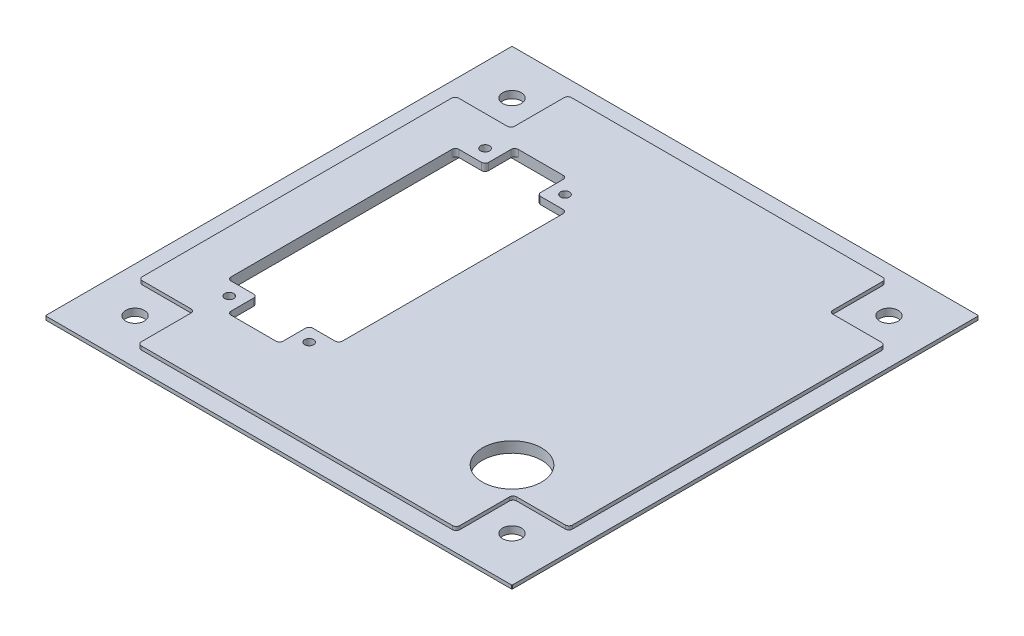
SolidWorks part; units mm, degrees
ref_plane "Front Plane" through (0, 0, 0) normal (0, 0, 1) x (1, 0, 0)
ref_plane "Top Plane" through (0, 0, 0) normal (0, 1, 0) x (1, 0, 0)
ref_plane "Right Plane" through (0, 0, 0) normal (1, 0, 0) x (0, 0, -1)
other "Configuration Table"
sketch "草图1" plane through (0, 0, 0) normal (0, 1, 0) x (1, 0, 0)
  line L1 (-65, 65) -> (65, 65)
  line L2 (-65, 65) -> (-65, -65)
  line L3 (-65, -65) -> (65, -65)
  line L4 (65, 65) -> (65, -65)
  line L5 (-65, 65) -> (65, -65) construction
  line L6 (-65, -65) -> (65, 65) construction
  point P0 (0, 0)
extrude "凸台-拉伸1" add sketch "草图1" along normal blind 3
sketch "草图2" plane through (0, 3, 0) normal (0, 1, 0) x (1, 0, 0)
  line L0 (52.5, 65) -> (52.5, 52.5) construction
  line L1 (65, 65) -> (-65, 65) construction
  line L2 (52.5, 52.5) -> (65, 52.5) construction
  line L3 (65, -65) -> (65, 65) construction
  line L4 (65, 52.5) -> (65, 65) construction
  line L5 (65, 65) -> (52.5, 65) construction
  circle A0 centre (52.5, 52.5) radius 2.6
  circle A1 centre (52.5, -52.5) radius 2.6
  circle A2 centre (-52.5, -52.5) radius 2.6
  circle A3 centre (-52.5, 52.5) radius 2.6
  point P19 (0, 0)
  dimension "D1" = 4
extrude "切除-拉伸1" cut sketch "草图2" against normal through all
sketch "草图4" plane through (0, 3, 0) normal (0, 1, 0) x (1, 0, 0)
  line L0 (65, 65) -> (44.3495, 65)
  line L1 (44.3495, 65) -> (44.3495, 44.0484)
  line L2 (44.3495, 44.0484) -> (65, 44.0484)
  line L3 (65, -65) -> (65, 65) construction
  line L4 (65, 44.0484) -> (65, 65)
  line L9 (-44.3495, -65) -> (-44.3495, -44.0484)
  line L10 (-44.3495, -44.0484) -> (-65, -44.0484)
  line L11 (-65, -44.0484) -> (-65, -65)
  line L12 (-65, -65) -> (-44.3495, -65)
  line L17 (65, -44.3495) -> (44.0484, -44.3495) [skipped]
  line L18 (44.0484, -44.3495) -> (44.0484, -65) [skipped]
  line L19 (44.0484, -65) -> (65, -65) [skipped]
  line L20 (65, -65) -> (65, -44.3495) [skipped]
  line L21 (-65, 44.3495) -> (-44.0484, 44.3495) [skipped]
  line L22 (-44.0484, 44.3495) -> (-44.0484, 65) [skipped]
  line L23 (-44.0484, 65) -> (-65, 65) [skipped]
  line L24 (-65, 65) -> (-65, 44.3495) [skipped]
  line L25 (0, 0) -> (0, -65) construction
  line L26 (-65, -65) -> (65, -65) construction
  line L27 (65, -65) -> (44.3495, -65)
  line L28 (65, -44.0484) -> (65, -65)
  line L29 (44.3495, -44.0484) -> (65, -44.0484)
  line L30 (44.3495, -65) -> (44.3495, -44.0484)
  line L31 (-65, 44.0484) -> (-65, 65)
  line L32 (-44.3495, 44.0484) -> (-65, 44.0484)
  line L33 (-44.3495, 65) -> (-44.3495, 44.0484)
  line L34 (-65, 65) -> (-44.3495, 65)
  point P22 (0, 0)
  dimension "D1" = 4
extrude "切除-拉伸2" cut sketch "草图4" against normal blind 1
sketch "草图5" plane through (0, 3, 0) normal (0, 1, 0) x (1, 0, 0)
  line L2 (44.3495, 65) -> (-44.3495, 65) construction
  line L5 (-44.3495, 65) -> (44.3495, 65)
  line L6 (44.3495, 65) -> (44.3495, 59.9)
  line L7 (44.3495, 65) -> (44.3495, 44.0484) construction
  line L8 (-44.3495, 65) -> (-44.3495, 59.9)
  line L9 (65, 44.0484) -> (59.9, 44.0484)
  line L10 (-44.3495, 59.9) -> (44.3495, 59.9)
  line L15 (44.3495, -65) -> (-44.3495, -65)
  line L16 (-44.3495, -65) -> (-44.3495, -59.9)
  line L17 (44.3495, -65) -> (44.3495, -59.9)
  line L18 (44.3495, -59.9) -> (-44.3495, -59.9)
  line L23 (-44.3495, 44.0484) -> (-44.3495, 65) construction
  line L24 (65, 44.3495) -> (65, -44.3495) [skipped]
  line L25 (65, -44.3495) -> (59.9, -44.3495) [skipped]
  line L26 (65, 44.3495) -> (59.9, 44.3495) [skipped]
  line L27 (59.9, 44.3495) -> (59.9, -44.3495) [skipped]
  line L28 (-65, -44.3495) -> (-65, 44.3495) [skipped]
  line L29 (-65, 44.3495) -> (-59.9, 44.3495) [skipped]
  line L30 (-65, -44.3495) -> (-59.9, -44.3495) [skipped]
  line L31 (-59.9, -44.3495) -> (-59.9, 44.3495) [skipped]
  line L32 (44.3495, 44.0484) -> (65, 44.0484) construction
  line L33 (65, -44.0484) -> (65, 44.0484) construction
  line L34 (44.3495, 44.0484) -> (65, 44.0484) construction
  line L35 (59.9, 44.0484) -> (59.9, -44.0484)
  line L36 (65, -44.0484) -> (44.3495, -44.0484) construction
  line L37 (59.9, -44.0484) -> (65, -44.0484)
  line L38 (65, -44.0484) -> (65, 44.0484)
  line L39 (0, 0) -> (0, 21.8453) construction
  line L40 (-65, -44.0484) -> (-65, 44.0484)
  line L41 (-59.9, -44.0484) -> (-65, -44.0484)
  line L42 (-59.9, 44.0484) -> (-59.9, -44.0484)
  line L43 (-65, 44.0484) -> (-59.9, 44.0484)
  point P27 (0, 0)
  dimension "D1" = 4
extrude "切除-拉伸3" cut sketch "草图5" against normal up to surface (1 mm away) up to face at (-54.6747, 2, 54.5242)
sketch "草图6" plane through (0, 0, 0) normal (0, -1, 0) x (-1, 0, 0)
  line L0 (60, 65) -> (60, -65) construction
  line L1 (60, 0) -> (47.5, 0) construction
  line L2 (47.5, -35) -> (47.5, 35)
  line L3 (42.5, -40) -> (21.5, -40)
  line L4 (16.5, -35) -> (16.5, 35)
  line L13 (21.5, 40) -> (42.5, 40)
  line L14 (65, -65) -> (-65, -65) construction
  arc A0 (42.5, -40) -> (47.5, -35) centre (42.5, -35) ccw
  arc A1 (21.5, -40) -> (16.5, -35) centre (21.5, -35) cw
  arc A2 (47.5, 35) -> (42.5, 40) centre (42.5, 35) ccw
  arc A3 (16.5, 35) -> (21.5, 40) centre (21.5, 35) cw
  point P9 (47.5, 0)
  dimension "D1" = 5
extrude "切除-拉伸4" cut sketch "草图6" against normal blind 3
sketch "草图7" plane through (0, 3, 0) normal (0, 1, 0) x (1, 0, 0)
  line L8 (-24.75, 40) -> (-24.75, 31.75)
  line L9 (-42.5, 40) -> (-21.5, 40) construction
  line L10 (-24.75, 31.75) -> (-16.5, 31.75)
  line L11 (-16.5, 35) -> (-16.5, -35) construction
  line L12 (-21.5, 40) -> (-24.75, 40)
  line L13 (-16.5, 35) -> (-16.5, 31.75)
  line L14 (-24.75, 31.75) -> (-17.9645, 38.5355) construction
  line L15 (-47.5, 0) -> (-16.5, 0) construction
  line L16 (-47.5, -35) -> (-47.5, 35) construction
  line L17 (-32, 0) -> (-32, 14.0496) construction
  line L18 (-21.5, 40) -> (-24.75, 40)
  line L19 (-16.5, 35) -> (-16.5, 31.75)
  line L20 (-24.75, 31.75) -> (-24.75, 40)
  line L21 (-16.5, 31.75) -> (-24.75, 31.75)
  line L22 (-24.75, 40) -> (-24.75, 31.75)
  line L23 (-24.75, 31.75) -> (-16.5, 31.75)
  line L24 (-21.5, 40) -> (-24.75, 40)
  line L25 (-16.5, 35) -> (-16.5, 31.75)
  line L26 (-21.5, 40) -> (-24.75, 40)
  line L27 (-16.5, 35) -> (-16.5, 31.75)
  line L28 (-24.75, 31.75) -> (-24.75, 40)
  line L29 (-16.5, 31.75) -> (-24.75, 31.75)
  line L30 (-24.75, -31.75) -> (-17.9645, -38.5355) construction
  line L31 (-16.5, -31.75) -> (-24.75, -31.75)
  line L32 (-24.75, -31.75) -> (-24.75, -40)
  line L33 (-16.5, -35) -> (-16.5, -31.75)
  line L34 (-21.5, -40) -> (-24.75, -40)
  line L35 (-16.5, -35) -> (-16.5, -31.75)
  line L36 (-21.5, -40) -> (-24.75, -40)
  line L37 (-24.75, -31.75) -> (-16.5, -31.75)
  line L38 (-24.75, -40) -> (-24.75, -31.75)
  line L39 (-16.5, -31.75) -> (-24.75, -31.75)
  line L40 (-24.75, -31.75) -> (-24.75, -40)
  line L41 (-16.5, -35) -> (-16.5, -31.75)
  line L42 (-21.5, -40) -> (-24.75, -40)
  line L43 (-16.5, -35) -> (-16.5, -31.75)
  line L44 (-21.5, -40) -> (-24.75, -40)
  line L45 (-24.75, -31.75) -> (-16.5, -31.75)
  line L46 (-24.75, -40) -> (-24.75, -31.75)
  line L47 (-39.25, -31.75) -> (-46.0355, -38.5355) construction
  line L48 (-39.25, -40) -> (-39.25, -31.75)
  line L49 (-39.25, -31.75) -> (-47.5, -31.75)
  line L50 (-42.5, -40) -> (-39.25, -40)
  line L51 (-47.5, -35) -> (-47.5, -31.75)
  line L52 (-42.5, -40) -> (-39.25, -40)
  line L53 (-47.5, -35) -> (-47.5, -31.75)
  line L54 (-39.25, -31.75) -> (-39.25, -40)
  line L55 (-47.5, -31.75) -> (-39.25, -31.75)
  line L56 (-39.25, -40) -> (-39.25, -31.75)
  line L57 (-39.25, -31.75) -> (-47.5, -31.75)
  line L58 (-42.5, -40) -> (-39.25, -40)
  line L59 (-47.5, -35) -> (-47.5, -31.75)
  line L60 (-42.5, -40) -> (-39.25, -40)
  line L61 (-47.5, -35) -> (-47.5, -31.75)
  line L62 (-39.25, -31.75) -> (-39.25, -40)
  line L63 (-47.5, -31.75) -> (-39.25, -31.75)
  line L64 (-39.25, 31.75) -> (-46.0355, 38.5355) construction
  line L65 (-47.5, 31.75) -> (-39.25, 31.75)
  line L66 (-39.25, 31.75) -> (-39.25, 40)
  line L67 (-47.5, 35) -> (-47.5, 31.75)
  line L68 (-42.5, 40) -> (-39.25, 40)
  line L69 (-47.5, 35) -> (-47.5, 31.75)
  line L70 (-42.5, 40) -> (-39.25, 40)
  line L71 (-39.25, 31.75) -> (-47.5, 31.75)
  line L72 (-39.25, 40) -> (-39.25, 31.75)
  line L73 (-47.5, 31.75) -> (-39.25, 31.75)
  line L74 (-39.25, 31.75) -> (-39.25, 40)
  line L75 (-47.5, 35) -> (-47.5, 31.75)
  line L76 (-42.5, 40) -> (-39.25, 40)
  line L77 (-47.5, 35) -> (-47.5, 31.75)
  line L78 (-42.5, 40) -> (-39.25, 40)
  line L79 (-39.25, 31.75) -> (-47.5, 31.75)
  line L80 (-39.25, 40) -> (-39.25, 31.75)
  circle A1 centre (-20.8723, 35.6277) radius 1.25
  circle A3 centre (-43.1277, 35.6277) radius 1.25
  arc A6 (-21.5, 40) -> (-16.5, 35) centre (-21.5, 35) cw
  arc A9 (-21.5, -40) -> (-16.5, -35) centre (-21.5, -35) ccw
  arc A10 (-42.5, -40) -> (-47.5, -35) centre (-42.5, -35) cw
  arc A13 (-42.5, 40) -> (-47.5, 35) centre (-42.5, 35) ccw
  circle A14 centre (-20.8723, -35.6277) radius 1.25
  circle A15 centre (-43.1277, -35.6277) radius 1.25
extrude "凸台-拉伸2" add sketch "草图7" against normal blind 2
fillet "圆角1" radius 1 4 edges at (-39.25, 2, 31.75) (-24.75, 2, 31.75) (-39.25, 2, -31.75) (-24.75, 2, -31.75)
sketch "草图15" plane through (0, 0, 0) normal (0, -1, 0) x (-1, 0, 0)
  line L0 (65, -65) -> (-65, -65) construction
  line L4 (-37, -37) -> (-65, -65) construction
  circle A0 centre (-37, -37) radius 8.25
  dimension "D1" = 28
  dimension "D2" = 45
extrude "切除-拉伸9" cut sketch "草图15" against normal through all
chamfer "倒角1" distance 1 angle 45 4 edges at (0, 0, -65) (-65, 0, 0) (0, 0, 65) (65, 0, 0)
chamfer "倒角2" distance 0.2 angle 45 4 edges at (-65, 1.5, -65) (-65, 1.5, 65) (65, 1.5, 65) (65, 1.5, -65)
fillet "圆角2" [suppressed] radius 0.5
fillet "圆角3" radius 1 12 edges at (-44.3495, 2.5, -59.9) (-44.3495, 2.5, -44.0484) (-59.9, 2.5, -44.0484) (-59.9, 2.5, 44.0484) (-44.3495, 2.5, 44.0484) (-44.3495, 2.5, 59.9) (44.3495, 2.5, 59.9) (44.3495, 2.5, 44.0484) (59.9, 2.5, 44.0484) (59.9, 2.5, -44.0484) (44.3495, 2.5, -44.0484) (44.3495, 2.5, -59.9)
fillet "圆角4" radius 1 8 edges at (-39.25, 2, 40) (-24.75, 2, 40) (-16.5, 2, 31.75) (-16.5, 2, -31.75) (-47.5, 2, 31.75) (-47.5, 2, -31.75) (-39.25, 2, -40) (-24.75, 2, -40)
